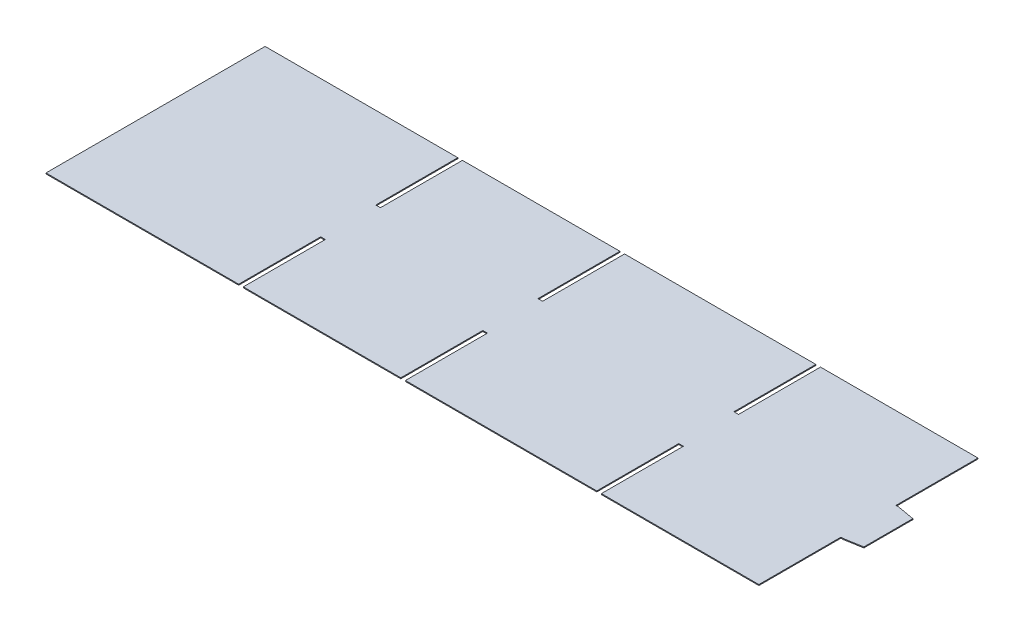
SolidWorks part; units mm, degrees
ref_plane "Front Plane" through (0, 0, 0) normal (0, 0, 1) x (1, 0, 0)
ref_plane "Top Plane" through (0, 0, 0) normal (0, 1, 0) x (1, 0, 0)
ref_plane "Right Plane" through (0, 0, 0) normal (1, 0, 0) x (0, 0, -1)
sketch "Sketch1" plane through (0, 0, 0) normal (0, 1, 0) x (1, 0, 0)
  line L0 (0, 0) -> (1544, 0) construction
  line L1 (0, 0) -> (0, 119) construction
  line L2 (0, 119) -> (1544, 119) construction
  line L3 (1544, 119) -> (1544, 0) construction
  line L4 (421, 119) -> (421, 0) construction
  line L5 (771, 119) -> (771, 0) construction
  line L6 (1194, 119) -> (1194, 0) construction
  line L7 (0, 0) -> (0, 296)
  line L8 (0, 296) -> (416, 296)
  line L9 (416, 296) -> (416, 119)
  line L10 (426, 119) -> (426, 296)
  line L11 (426, 296) -> (766, 296)
  line L12 (766, 296) -> (766, 119)
  line L13 (766, 119) -> (776, 119)
  line L14 (776, 119) -> (776, 296)
  line L15 (776, 296) -> (1189, 296)
  line L16 (1189, 296) -> (1189, 119)
  line L17 (1189, 119) -> (1199, 119)
  line L18 (1199, 119) -> (1199, 296)
  line L19 (1199, 296) -> (1539, 296)
  line L20 (1539, 296) -> (1539, 119)
  line L21 (1544, 59.5) -> (0, 59.5) construction
  line L22 (1194, 119) -> (1199, 119) construction
  line L23 (1199, -177) -> (1539, -177)
  line L24 (1199, 0) -> (1199, -177)
  line L25 (1189, 0) -> (1199, 0)
  line L26 (1189, -177) -> (1189, 0)
  line L27 (776, -177) -> (1189, -177)
  line L28 (776, 0) -> (776, -177)
  line L29 (766, 0) -> (776, 0)
  line L30 (766, -177) -> (766, 0)
  line L31 (426, -177) -> (766, -177)
  line L32 (426, 0) -> (426, -177)
  line L33 (416, -177) -> (416, 0)
  line L34 (0, -177) -> (416, -177)
  line L35 (0, 0) -> (0, -177)
  line L36 (1544, 119) -> (1539, 119)
  line L37 (1544, 119) -> (1582, 112.2996)
  line L38 (1582, 112.2996) -> (1582, 6.7004)
  line L39 (416, 119) -> (426, 119)
  line L40 (416, 0) -> (426, 0)
  line L41 (1544, 0) -> (1539, 0)
  line L42 (1539, 0) -> (1539, -177)
  line L43 (1544, 0) -> (1582, 6.7004)
  point P42 (1582, 59.5)
  dimension "D1" = 421
  dimension "D2" = 350
  dimension "D3" = 423
  dimension "D4" = 350
  dimension "D5" = 119
  dimension "D6" = 10
  dimension "D7" = 80
  dimension "D12" = 473
  dimension "D13" = 38
extrude "Boss-Extrude1" add sketch "Sketch1" along normal blind 2
